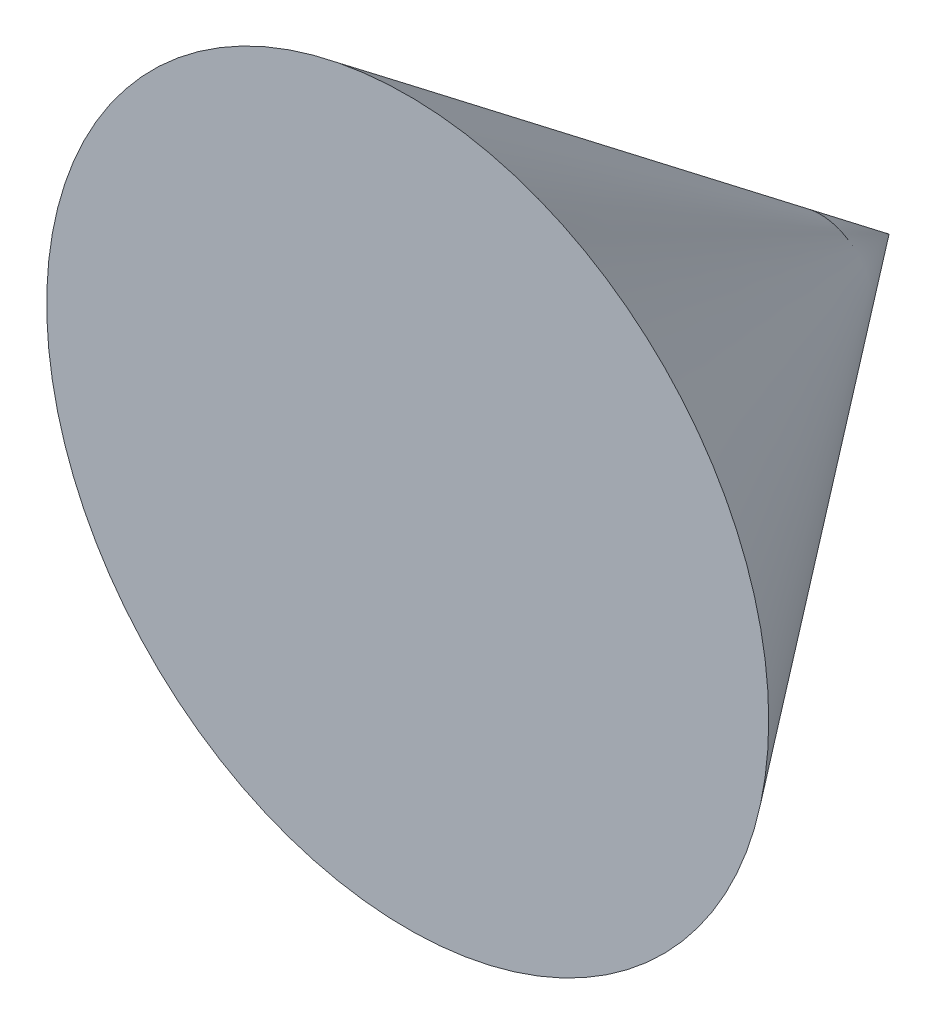
SolidWorks part; units mm, degrees
ref_plane "前视基准面" through (0, 0, 0) normal (0, 0, 1) x (1, 0, 0)
ref_plane "上视基准面" through (0, 0, 0) normal (0, 1, 0) x (1, 0, 0)
ref_plane "右视基准面" through (0, 0, 0) normal (1, 0, 0) x (0, 0, -1)
other "Configuration Table"
sketch "草图1" plane through (0, 0, 0) normal (0, 1, 0) x (1, 0, 0)
  line L0 (0, 0) -> (0, 200) construction
  line L1 (0, 0) -> (150, 0)
  line L2 (150, 0) -> (0, 200)
  line L3 (0, 0) -> (0, 200)
revolve "旋转1" add sketch "草图1" angle 360 about L0
